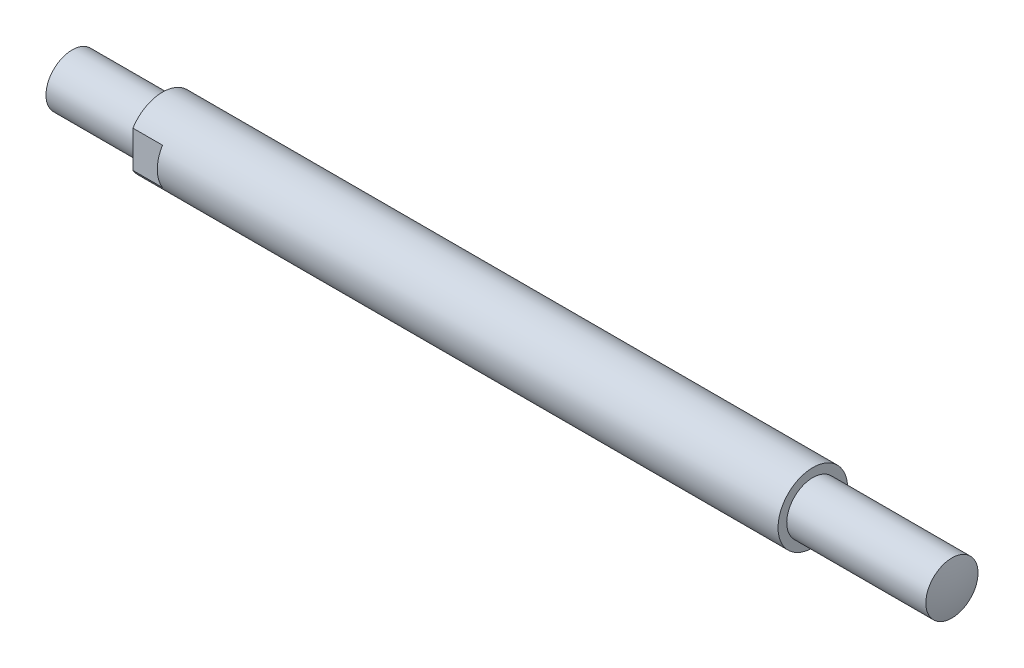
SolidWorks part; units mm, degrees
ref_plane "Front Plane" through (0, 0, 0) normal (0, 0, 1) x (1, 0, 0)
ref_plane "Top Plane" through (0, 0, 0) normal (0, 1, 0) x (1, 0, 0)
ref_plane "Right Plane" through (0, 0, 0) normal (1, 0, 0) x (0, 0, -1)
sketch "Sketch1" plane through (0, 0, 0) normal (0, 0, 1) x (1, 0, 0)
  line L0 (0, 0) -> (23549.1298, 0) construction
  line L1 (0, 0) -> (0, -23549.1298) construction
  line L2 (-239, 15) -> (-187, 15)
  line L3 (-187, 15) -> (-187, 20)
  line L4 (-187, 20) -> (187, 20)
  line L5 (187, 20) -> (187, 15)
  line L6 (187, 15) -> (267, 15)
  line L7 (-241, 0) -> (269, 0)
  arc A0 (-239, 15) -> (-241, 0) centre (-183.75, 0) ccw
  arc A1 (267, 15) -> (269, 0) centre (211.75, 0) cw
  point P16 (0, 20)
  dimension "D1" = 80
  dimension "D2" = 52
  dimension "D3" = 30
  dimension "D4" = 40
  dimension "D5" = 2
  dimension "D6" = 2
  dimension "D7" = 510
revolve "Revolve1" add sketch "Sketch1" angle 360 about L7
cosmetic thread "Cosmetic Thread1" parameters "D1"=36, "D2"=26.158
cosmetic thread "Cosmetic Thread2" parameters "D1"=80, "D2"=26.158
sketch "Sketch2" plane through (-187, 0, 0) normal (-1, 0, 0) x (0, 0, 1)
  line L0 (0, 0) -> (0, -28.4483) construction
  line L1 (17, 17.8844) -> (30.8071, 17.8844)
  line L2 (17, 17.8844) -> (17, -16.1238)
  line L3 (17, -16.1238) -> (30.8071, -16.1238)
  line L4 (30.8071, 17.8844) -> (30.8071, -16.1238)
  line L5 (-25.1546, 17.3284) -> (-17, 17.3284)
  line L6 (-25.1546, 17.3284) -> (-25.1546, -21.9617)
  line L7 (-25.1546, -21.9617) -> (-17, -21.9617)
  line L8 (-17, 17.3284) -> (-17, -21.9617)
  dimension "D1" = 34
extrude "Cut-Extrude1" cut sketch "Sketch2" against normal blind 17
